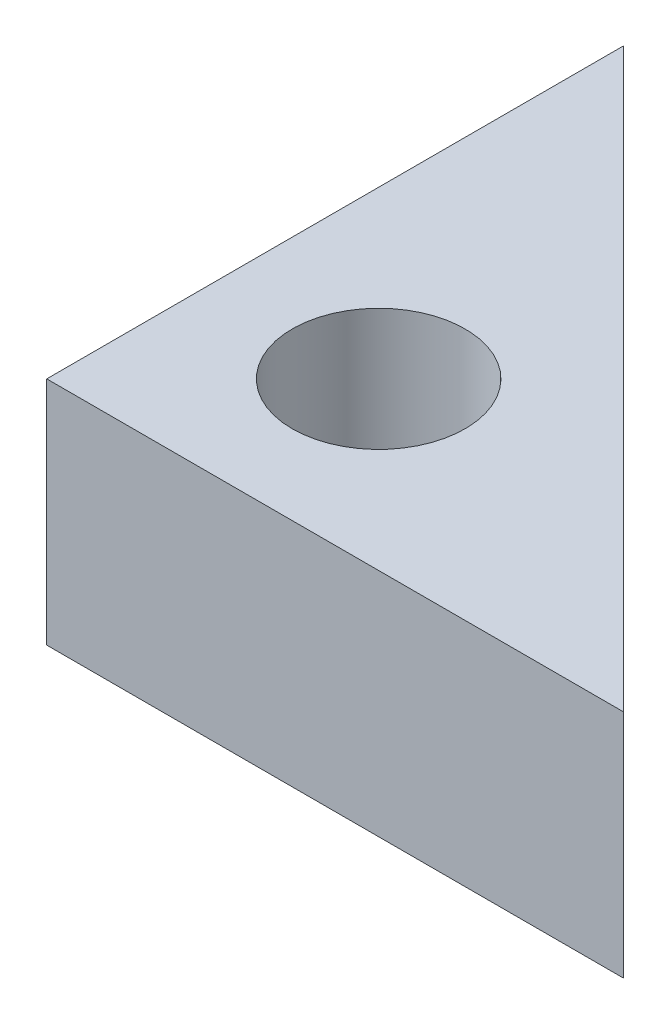
SolidWorks part; units mm, degrees
ref_plane "Front Plane" through (0, 0, 0) normal (0, 0, 1) x (1, 0, 0)
ref_plane "Top Plane" through (0, 0, 0) normal (0, 1, 0) x (1, 0, 0)
ref_plane "Right Plane" through (0, 0, 0) normal (1, 0, 0) x (0, 0, -1)
sketch "Sketch1" plane through (0, 0, 0) normal (0, 1, 0) x (1, 0, 0)
  line L0 (0, 10) -> (0, 0)
  line L1 (0, 0) -> (10, 0)
  line L2 (10, 0) -> (0, 10)
  line L3 (0, 0) -> (5, 5) construction
  circle A0 centre (2.8787, 2.8787) radius 1.5
  point P4 (2.8787, 2.8787)
  point P6 (3.0568, 3.0568)
  dimension "D3" = 3
  dimension "D4" = 3
  dimension "D1" = 10
  dimension "D2" = 10
extrude "Boss-Extrude1" add sketch "Sketch1" along normal blind 4
